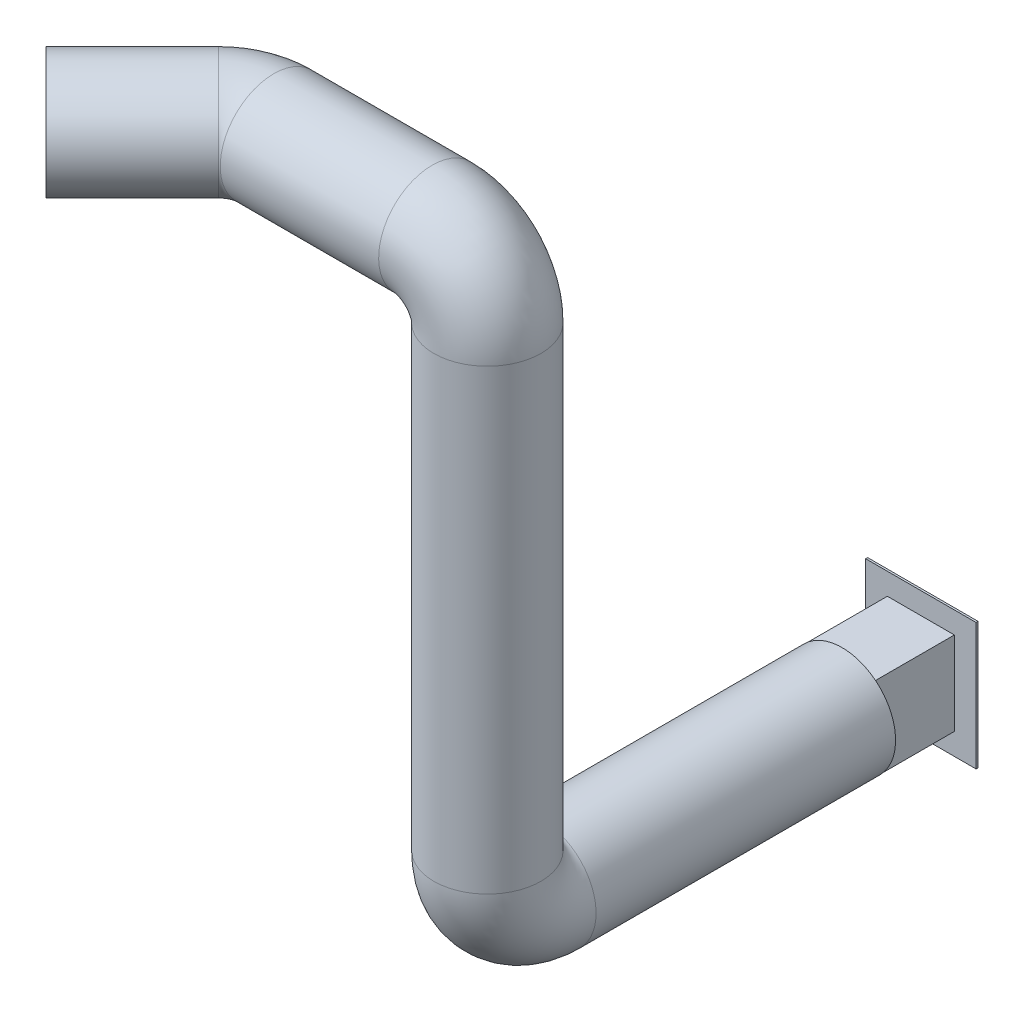
SolidWorks part; units mm, degrees
ref_plane "Alzado" through (0, 0, 0) normal (0, 0, 1) x (1, 0, 0)
ref_plane "Planta" through (0, 0, 0) normal (0, 1, 0) x (1, 0, 0)
ref_plane "Vista lateral" through (0, 0, 0) normal (1, 0, 0) x (0, 0, -1)
sketch "Croquis1" plane through (0, 0, 0) normal (0, 0, 1) x (1, 0, 0)
  line L0 (70, 0) -> (70, -161) construction
  line L1 (0, 0) -> (140, 0)
  line L2 (0, 0) -> (0, -161)
  line L3 (0, -161) -> (140, -161)
  line L4 (140, 0) -> (140, -161)
  line L6 (30, -131) -> (110, -131)
  line L7 (30, -131) -> (30, -30)
  line L8 (30, -30) -> (110, -30)
  line L9 (110, -131) -> (110, -30)
  line L10 (30, -131) -> (110, -30) construction
  line L11 (30, -30) -> (110, -131) construction
  point P8 (70, -80.5)
  dimension "D1" = 140
  dimension "D2" = 161
  dimension "D3" = 30
  dimension "D4" = 30
extrude "Saliente-Extruir1" add sketch "Croquis1" along normal blind 2.5
sketch "Croquis2" plane through (0, 0, 2.5) normal (0, 0, 1) x (1, 0, 0)
  line L0 (27.5, -27.5) -> (27.5, -133.5)
  line L1 (30, -30) -> (110, -30)
  line L2 (30, -30) -> (30, -131)
  line L3 (30, -131) -> (110, -131)
  line L4 (110, -30) -> (110, -131)
  line L5 (27.5, -133.5) -> (112.5, -133.5)
  line L6 (112.5, -27.5) -> (112.5, -133.5)
  line L7 (27.5, -27.5) -> (112.5, -27.5)
  dimension "D1" = 2.5
extrude "Saliente-Extruir2" add sketch "Croquis2" along normal blind 100
sketch "Croquis3" plane through (0, 0, 102.5) normal (0, 0, 1) x (1, 0, 0)
  line L0 (70, -27.5) -> (70, -133.5) construction
  line L1 (112.5, -27.5) -> (27.5, -27.5) construction
  line L2 (27.5, -133.5) -> (112.5, -133.5) construction
  circle A0 centre (70, -80.5) radius 67.9356
extrude "Saliente-Extruir3" add sketch "Croquis3" along normal blind 100
sketch3d "Croquis3D1"
  line L0 (70, -80.5, 202.5) -> (70, -80.5, 482.5)
  line L1 (70, -80.5, 202.5) -> (70, -80.5, 102.5) construction
  line L2 (70, -10.5, 552.5) -> (70, 569.5, 552.5)
  line L3 (0, 639.5, 552.5) -> (-201.0051, 639.5, 552.5)
  line L4 (-230, 639.5, 552.5) -> (-230, 639.5, 682.5) construction
  line L5 (-230, 639.5, 682.5) -> (-360, 639.5, 682.5) construction
  line L6 (-360, 639.5, 682.5) -> (-250.5025, 639.5, 573.0025)
  arc A0 (-201.0051, 639.5, 552.5) -> (-250.5025, 639.5, 573.0025) centre (-201.0051, 639.5, 622.5) ccw
  arc A1 (70, 569.5, 552.5) -> (0, 639.5, 552.5) centre (0, 569.5, 552.5) ccw
  arc A2 (70, -80.5, 482.5) -> (70, -10.5, 552.5) centre (70, -10.5, 482.5) ccw
  point P10 (-230, 639.5, 552.5)
  point P12 (-201.0051, 709.5, 622.5)
  point P15 (70, 639.5, 552.5)
  point P16 (0, 569.5, 622.5)
  point P19 (70, -80.5, 552.5)
  point P20 (0, -10.5, 482.5)
  dimension "D6" = 70
  dimension "D1" = 350
  dimension "D2" = 720
  dimension "D3" = 300
  dimension "D4" = 130
  dimension "D5" = 130
sketch "Croquis4" plane through (0, 0, 202.5) normal (0, 0, 1) x (1, 0, 0)
  circle A0 centre (70, -80.5) radius 67.9356
sweep "Barrer1" add profiles "Croquis4" path "Croquis3D1"
